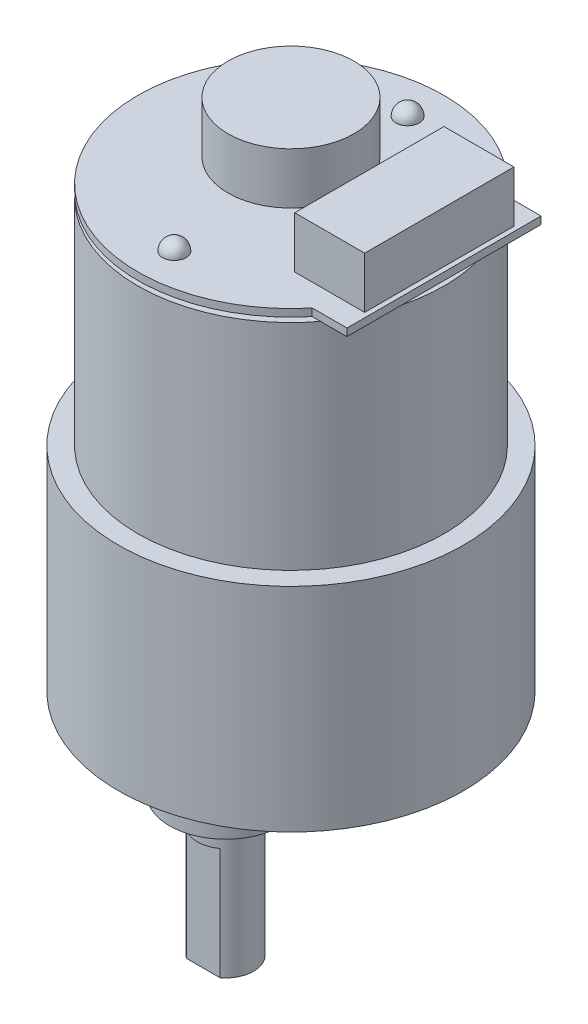
SolidWorks part; units mm, degrees
ref_plane "Front Plane" through (0, 0, 0) normal (1, 0, 0) x (0, 1, 0)
ref_plane "Top Plane" through (0, 0, 0) normal (0, 0, 1) x (0, 1, 0)
ref_plane "Right Plane" through (0, 0, 0) normal (0, 1, 0) x (-1, 0, 0)
sketch "Sketch1" plane through (0, 0, 0) normal (0, 1, 0) x (-1, 0, 0)
  circle A0 centre (0, 0) radius 16.4
  dimension "D1" = 32.8
extrude "Boss-Extrude1" add sketch "Sketch1" along normal blind 23
sketch "Sketch2" plane through (0, 23, 0) normal (0, 1, 0) x (-1, 0, 0)
  line L0 (0, 12.5) -> (0, -12.5) construction
  circle A0 centre (0, 12.5) radius 1.25
  circle A1 centre (0, -12.5) radius 1.25
  point P2 (4.2879, -3.2162)
  point P3 (0.0984, 12.5)
  point P4 (0, 0)
  point P9 (0, 0)
  point P10 (0, -12.6002)
  dimension "D2" = 2.5
  dimension "D3" = 2.5
  dimension "D4" = 25
extrude "Boss-Extrude2" add sketch "Sketch2" along normal blind 0.5
sketch "Sketch4" plane through (0, 0, 0) normal (0, -1, 0) x (1, 0, 0)
  circle A0 centre (0, 0) radius 18.5
  dimension "D1" = 37
extrude "Boss-Extrude4" add sketch "Sketch4" along normal blind 22.8
sketch "Sketch5" plane through (0, -22.8, 0) normal (0, -1, 0) x (1, 0, 0)
  line L0 (0, 0) -> (0, 7) construction
  arc A0 (-8.8112, 8.8664) -> (8.8112, 8.8664) centre (0, 0) ccw
  arc A1 (-8.8112, 8.8664) -> (8.8112, 8.8664) centre (0, 7) ccw
  dimension "D2" = 12.5
  dimension "D1" = 7
extrude "Cut-Extrude1" cut sketch "Sketch5" against normal blind 1
sketch "Sketch6" plane through (0, -22.8, 0) normal (0, -1, 0) x (1, 0, 0)
  line L0 (0, 0) -> (0, 7) construction
  line L1 (0, -2.0067) -> (0, 0.9933) construction
  arc A0 (-8.8112, 8.8664) -> (8.8112, 8.8664) centre (0, 7) ccw construction
  circle A1 centre (0, 7) radius 6.0067
  dimension "D1" = 7
  dimension "D2" = 3
extrude "Boss-Extrude5" add sketch "Sketch6" along normal blind 6
sketch "Sketch7" plane through (0, -28.8, 0) normal (0, -1, 0) x (1, 0, 0)
  circle A0 centre (0, 7) radius 3
  dimension "D1" = 6
extrude "Boss-Extrude6" add sketch "Sketch7" along normal blind 15
sketch "Sketch8" plane through (0, -43.8, 0) normal (0, -1, 0) x (1, 0, 0)
  line L0 (0, 4) -> (0, 9.4) construction
  line L1 (-1.8, 9.4) -> (1.8, 9.4)
  circle A0 centre (0, 7) radius 3 construction
  circle A1 centre (0, 7) radius 3 construction
  circle A2 centre (0, 7) radius 3 construction
  arc A3 (1.8, 9.4) -> (-1.8, 9.4) centre (0, 7) ccw
  point P13 (0, 9.4)
  dimension "D2" = 6
  dimension "D1" = 5.4
extrude "Cut-Extrude2" cut sketch "Sketch8" against normal blind 12
sketch "Sketch9" plane through (0, 23.5, 0) normal (0, 1, 0) x (-1, 0, 0)
  line L0 (0, 10.4) -> (0, -10.4) construction
  line L1 (-12.6807, 10.4) -> (-16.4, 10.4)
  line L2 (-16.4, 10.4) -> (-16.4, -10.4)
  line L3 (-16.4, -10.4) -> (-12.6807, -10.4)
  line L4 (0, -10.4) -> (-12.6807, -10.4) construction
  arc A0 (-12.6807, 10.4) -> (-12.6807, -10.4) centre (0, 0) cw
  circle A1 centre (0, 0) radius 16.4 construction
  circle A2 centre (0, 0) radius 16.4 construction
  point P1 (-12.6424, -10.4466)
  point P10 (0, 0)
  dimension "D1" = 20.8
extrude "Boss-Extrude7" add sketch "Sketch9" along normal blind 0.8
sketch "Sketch10" plane through (0, 24.3, 0) normal (0, 1, 0) x (-1, 0, 0)
  line L0 (0, 12.5) -> (0, -12.5) construction
  line L1 (0, 13.75) -> (0, 11.25)
  line L2 (0, -11.25) -> (0, -13.75)
  arc A2 (0, 11.25) -> (0, 13.75) centre (0, 12.5) ccw
  arc A3 (0, -11.25) -> (0, -13.75) centre (0, -12.5) cw
  point P5 (0, 0)
  dimension "D2" = 2.5
  dimension "D3" = 2.5
  dimension "D1" = 25
revolve "Revolve4" add sketch "Sketch10" angle 180 about L0
sketch "Sketch13" plane through (0, 24.3, 0) normal (0, 1, 0) x (-1, 0, 0)
  circle A0 centre (0, 0) radius 1
  dimension "D1" = 2
extrude "Boss-Extrude9" add sketch "Sketch13" along normal blind 2.5
sketch "Sketch14" plane through (0, 26.8, 0) normal (0, 1, 0) x (-1, 0, 0)
  circle A0 centre (0, 0) radius 6.75
  dimension "D1" = 13.5
extrude "Boss-Extrude10" add sketch "Sketch14" along normal blind 5.5
sketch "Sketch15" plane through (0, 24.3, 0) normal (0, 1, 0) x (-1, 0, 0)
  line L0 (-8.4, -8) -> (-8.4, 8)
  line L1 (-8.4, -8) -> (-15.9, -8)
  line L2 (-8.4, 8) -> (-15.9, 8)
  line L3 (-15.9, -8) -> (-15.9, 8)
  line L4 (-8.4, -8) -> (-15.9, 8) construction
  line L5 (-8.4, 8) -> (-15.9, -8) construction
  line L6 (-16.4, 10.4) -> (-16.4, -10.4) construction
  line L7 (0, 0) -> (-16.4, 0) construction
  point P1 (-12.15, 0)
  point P10 (-12.15, 0)
  dimension "D1" = 0.5
  dimension "D2" = 7.5
  dimension "D3" = 16
extrude "Boss-Extrude11" add sketch "Sketch15" along normal blind 5.5
